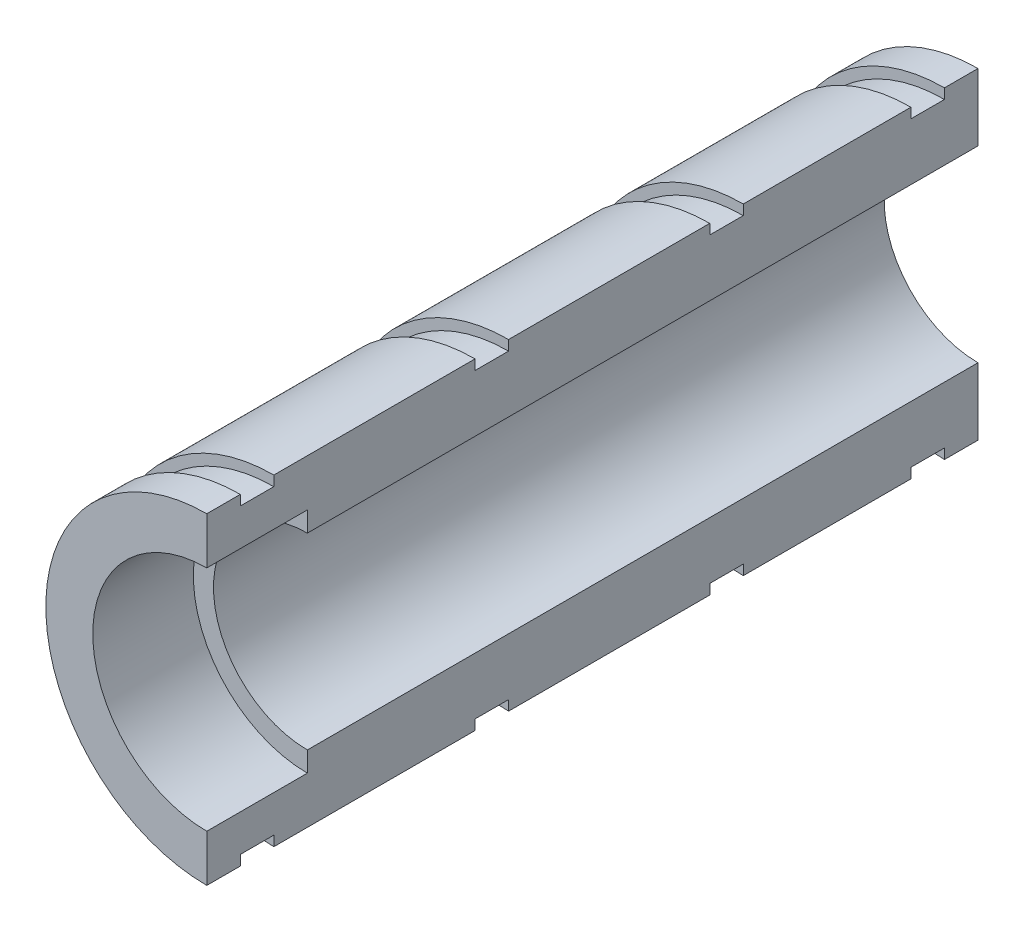
SolidWorks part; units mm, degrees
ref_plane "Front Plane" through (0, 0, 0) normal (0, 0, 1) x (1, 0, 0)
ref_plane "Top Plane" through (0, 0, 0) normal (0, 1, 0) x (1, 0, 0)
ref_plane "Right Plane" through (0, 0, 0) normal (1, 0, 0) x (0, 0, -1)
sketch "Sketch1" plane through (0, 0, 0) normal (0, 0, 1) x (1, 0, 0)
  circle A0 centre (0, 0) radius 14
  circle A1 centre (0, 0) radius 24
  dimension "D1" = 28
  dimension "D2" = 48
extrude "Boss-Extrude1" add sketch "Sketch1" along normal blind 115
sketch "Sketch2" plane through (0, 0, 115) normal (0, 0, 1) x (1, 0, 0)
  line L1 (0, 27.3296) -> (30.5605, 27.3296)
  line L2 (0, 27.3296) -> (0, -28.3361)
  line L3 (0, -28.3361) -> (30.5605, -28.3361)
  line L4 (30.5605, 27.3296) -> (30.5605, -28.3361)
extrude "Cut-Extrude1" cut sketch "Sketch2" against normal blind 130
sketch "Sketch3" plane through (0, 0, 115) normal (0, 0, 1) x (1, 0, 0)
  circle A0 centre (0, 0) radius 17
  dimension "D1" = 34
extrude "Cut-Extrude2" cut sketch "Sketch3" against normal blind 15
ref_plane "Plane1" through (0, 0, 35) normal (0, 0, -1) x (-1, 0, 0)
sketch "Sketch4" plane through (0, 0, 35) normal (0, 0, -1) x (-1, 0, 0)
  circle A0 centre (0, 0) radius 22.5
  circle A1 centre (0, 0) radius 29.3487
  dimension "D1" = 45
extrude "Cut-Extrude3" cut sketch "Sketch4" against normal blind 5
ref_plane "Plane2" through (0, 0, 70) normal (0, 0, -1) x (-1, 0, 0)
sketch "Sketch5" plane through (0, 0, 70) normal (0, 0, -1) x (-1, 0, 0)
  circle A0 centre (0, 0) radius 22.5
  circle A1 centre (0, 0) radius 32.2275
  dimension "D1" = 45
extrude "Cut-Extrude4" cut sketch "Sketch5" against normal blind 5
ref_plane "Plane3" through (0, 0, 105) normal (0, 0, 1) x (1, 0, 0)
sketch "Sketch6" plane through (0, 0, 105) normal (0, 0, 1) x (1, 0, 0)
  circle A0 centre (0, 0) radius 22.5
  circle A1 centre (0, 0) radius 32.4095
  dimension "D1" = 45
extrude "Cut-Extrude5" cut sketch "Sketch6" along normal blind 5
ref_plane "Plane4" through (0, 0, 10) normal (0, 0, -1) x (-1, 0, 0)
sketch "Sketch7" plane through (0, 0, 10) normal (0, 0, -1) x (-1, 0, 0)
  circle A0 centre (0, 0) radius 22.5
  circle A1 centre (0, 0) radius 39.3564
  dimension "D1" = 45
extrude "Cut-Extrude6" cut sketch "Sketch7" along normal blind 5
